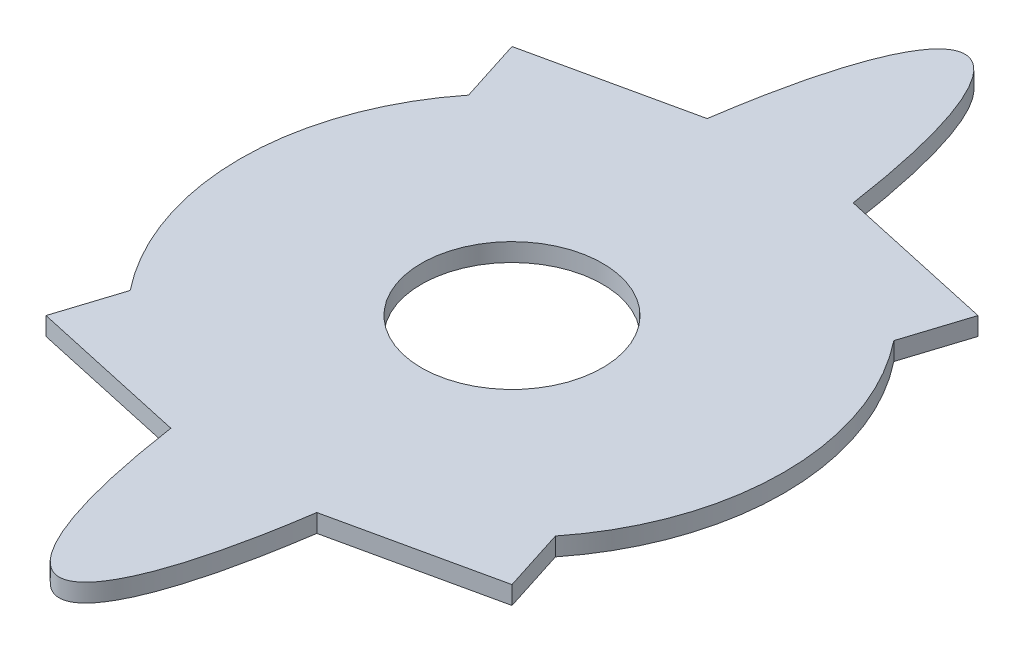
SolidWorks part; units mm, degrees
material "Miedź"
ref_plane "Płaszczyzna przednia" through (0, 0, 0) normal (0, 0, 1) x (1, 0, 0)
ref_plane "Płaszczyzna górna" through (0, 0, 0) normal (0, 1, 0) x (1, 0, 0)
ref_plane "Płaszczyzna prawa" through (0, 0, 0) normal (1, 0, 0) x (0, 0, -1)
sketch "Szkic1" plane through (0, 0, 0) normal (0, 1, 0) x (1, 0, 0)
  line L0 (-61.0765, 17.9546) -> (45.7753, 41.4402)
  line L1 (-50, 0) -> (50, 0) construction
  line L2 (0, 50) -> (0, -50) construction
  line L3 (61.0765, 17.9546) -> (-45.7753, 41.4402)
  line L4 (-61.0765, -17.9546) -> (45.7753, -41.4402)
  line L5 (61.0765, -17.9546) -> (-45.7753, -41.4402)
  line L6 (34.2973, 52.5744) -> (-2.1147, -61.4701)
  line L7 (-34.2973, 52.5744) -> (2.1147, -61.4701)
  line L8 (34.2973, -52.5744) -> (-2.1147, 61.4701)
  line L9 (-34.2973, -52.5744) -> (2.1147, 61.4701)
  circle A0 centre (0, 0) radius 50
  circle A1 centre (0, 0) radius 30
  circle A2 centre (0, 0) radius 10
  ellipse E0 centre (0, 0) end of major axis (0, 50) minor radius 10
  ellipse E1 centre (0, 0) end of major axis (0, -50) minor radius 30
  ellipse E2 centre (0, 0) end of major axis (50, 0) minor radius 30
  point P5 (-25.7248, 25.7248)
  point P20 (-8.0582, 29.6078)
  point P34 (25.7248, -25.7248)
  point P39 (8.0582, -29.6078)
  point P41 (25.7248, 25.7248)
  dimension "D1" = 100
  dimension "D2" = 60
  dimension "D3" = 20
extrude "Dodanie-wyciągnięcie1" add sketch "Szkic1" along normal blind 2
